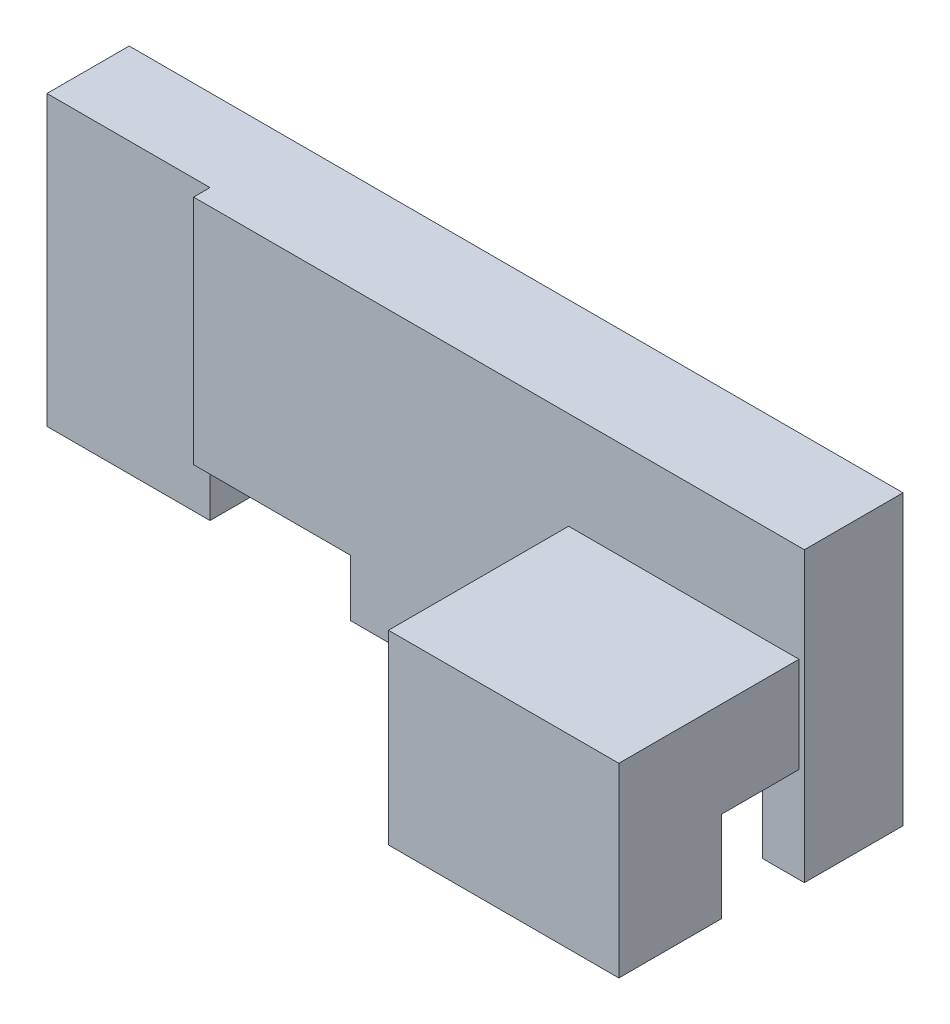
SolidWorks part; units mm, degrees
ref_plane "Płaszczyzna przednia" through (0, 0, 0) normal (0, 0, 1) x (1, 0, 0)
ref_plane "Płaszczyzna górna" through (0, 0, 0) normal (0, 1, 0) x (1, 0, 0)
ref_plane "Płaszczyzna prawa" through (0, 0, 0) normal (1, 0, 0) x (0, 0, -1)
ref_plane "Płaszczyzna6" through (0, -690, 0) normal (0, 1, 0) x (1, 0, 0)
sketch "Szkic4" plane through (0, -690, 0) normal (0, 1, 0) x (1, 0, 0)
  line L0 (-7.033, -0.5427) -> (-878.3342, -0.5427) construction
  line L1 (-7.033, -0.5427) -> (2679.9434, -0.5427) construction
  line L2 (-878.3342, -0.5427) -> (-878.3342, -35.5427) construction
  line L3 (-878.3342, -35.5427) -> (2591.8722, -35.5427) construction
  line L4 (-205.75, -205.75) -> (-290.75, -205.75) construction
  line L5 (-290.75, -205.75) -> (-290.75, -35.5427)
  line L6 (-290.75, -35.5427) -> (-895.75, -35.5427)
  line L7 (-895.75, -35.5427) -> (-895.75, -340.5427)
  line L8 (-895.75, -340.5427) -> (-290.75, -340.5427)
  line L9 (-290.75, -340.5427) -> (-290.75, -205.75)
  line L10 (205.75, -205.75) -> (290.75, -205.75) construction
  line L11 (290.75, -401.5) -> (1239.25, -401.5)
  line L12 (290.75, -205.75) -> (290.75, -35.5427)
  line L13 (1324.25, -205.75) -> (1239.25, -205.75) construction
  line L14 (1239.25, -205.75) -> (1239.25, -35.5427)
  line L15 (1239.25, -35.5427) -> (290.75, -35.5427)
  line L16 (290.75, -205.75) -> (290.75, -401.5)
  line L17 (1239.25, -205.75) -> (1239.25, -401.5)
  line L18 (1735.75, -205.75) -> (1820.75, -205.75) construction
  line L19 (1820.75, -205.75) -> (1820.75, -35.5427)
  line L20 (1735.75, -205.75) -> (1975.75, -205.75) construction
  line L21 (1820.75, -401.5) -> (1975.75, -401.5)
  line L22 (1820.75, -205.75) -> (1820.75, -401.5)
  line L23 (1975.75, -401.5) -> (1975.75, -35.5427)
  line L24 (1975.75, -35.5427) -> (1820.75, -35.5427)
  line L25 (-205.75, -205.75) -> (-895.75, -205.75) construction
  arc A0 (-91.4382, -21.4347) -> (91.4382, -21.4347) centre (0, -205.75) ccw construction
  arc A1 (1438.5618, -21.4347) -> (1621.4382, -21.4347) centre (1530, -205.75) ccw construction
  dimension "D1" = 85
  dimension "D2" = 690
  dimension "D3" = 85
  dimension "D4" = 85
  dimension "D5" = 85
  dimension "D6" = 240
extrude "Dodanie-wyciągnięcie9" add sketch "Szkic4" along normal blind 210
sketch "Szkic6" plane through (0, -480, 0) normal (0, 1, 0) x (1, 0, 0)
  line L0 (1975.75, -35.5427) -> (-895.75, -35.5427)
  line L1 (-895.75, -35.5427) -> (-895.75, -340.5427)
  line L2 (-895.75, -340.5427) -> (-290.75, -340.5427)
  line L3 (0, -411.5) -> (-290.75, -411.5) construction
  line L4 (-290.75, -411.5) -> (-290.75, -401.5) construction
  line L5 (-290.75, -340.5427) -> (-290.75, -401.5)
  line L6 (-290.75, -401.5) -> (1975.75, -401.5)
  line L9 (1975.75, -401.5) -> (1975.75, -35.5427)
  arc A0 (-91.4382, -21.4347) -> (91.4382, -21.4347) centre (0, -205.75) ccw construction
extrude "Dodanie-wyciągnięcie10" add sketch "Szkic6" along normal blind 860
ref_plane "Płaszczyzna7" through (0, -452, 0) normal (0, 1, 0) x (1, 0, 0)
sketch "Szkic7" plane through (0, -452, 0) normal (0, 1, 0) x (1, 0, 0)
  line L0 (1530, 0) -> (1530, -710) construction
  line L3 (1975.75, -1090) -> (1120.75, -1090)
  line L4 (1120.75, -1090) -> (1120.75, -710)
  line L5 (1120.75, -710) -> (1975.75, -710)
  line L7 (1975.75, -710) -> (1975.75, -1090)
extrude "Dodanie-wyciągnięcie11" add sketch "Szkic7" along normal blind 490 and the other way blind 200 separate body
sketch "Szkic8" plane through (0, 0, 401.5) normal (0, 0, 1) x (1, 0, 0)
  line L0 (1239.25, -480) -> (1820.75, -480) construction
  line L2 (1239.25, -480) -> (1239.25, -457.3)
  line L4 (1239.25, -457.3) -> (1820.75, -457.3)
  line L5 (1820.75, -480) -> (1820.75, -457.3)
  line L6 (1239.25, -480) -> (1820.75, -480)
extrude "Wytnij-wyciągnięcie1" cut sketch "Szkic8" against normal blind 470
sketch "Szkic9" plane through (-895.75, 0, 0) normal (-1, 0, 0) x (0, 0, 1)
  line L0 (0, 255) -> (85, 255)
  line L3 (85, 255) -> (85, -255)
  line L4 (85, -255) -> (0, -255)
  line L5 (0, -255) -> (0, 255)
  point P5 (0, 0)
  dimension "D1" = 85
  dimension "D2" = 510
extrude "Wytnij-wyciągnięcie2" cut sketch "Szkic9" against normal blind 690
ref_plane "Płaszczyzna8" through (0, 0, 421.5) normal (0, 0, 1) x (1, 0, 0)
sketch "Szkic11" plane through (0, 0, 421.5) normal (0, 0, 1) x (1, 0, 0)
  line L0 (1332.8266, -476.2316) -> (1332.8266, -316.2316) construction
  line L1 (1324.25, -476.2316) -> (1735.75, -476.2316) construction
  line L2 (1120.75, -652) -> (1120.75, 38) construction
  line L3 (1120.75, -316.2316) -> (1975.75, -316.2316)
  line L4 (1120.75, -316.2316) -> (1120.75, 38)
  line L5 (1120.75, 38) -> (1975.75, 38)
  line L6 (1975.75, -316.2316) -> (1975.75, 38)
  dimension "D1" = 160
extrude "Dodanie-wyciągnięcie12" add sketch "Szkic11" along normal blind 290
